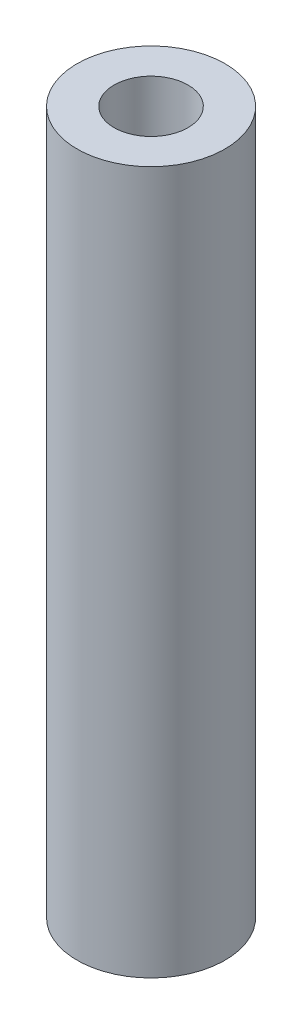
SolidWorks part; units mm, degrees
ref_plane "Front Plane" through (0, 0, 0) normal (0, 0, 1) x (1, 0, 0)
ref_plane "Top Plane" through (0, 0, 0) normal (0, 1, 0) x (1, 0, 0)
ref_plane "Right Plane" through (0, 0, 0) normal (1, 0, 0) x (0, 0, -1)
sketch "Sketch1" plane through (0, 0, 0) normal (0, 1, 0) x (1, 0, 0)
  circle A0 centre (0, 0) radius 2.54
  circle A1 centre (0, 0) radius 5.08
  dimension "D1" = 5.08
  dimension "D2" = 10.16
extrude "Boss-Extrude1" add sketch "Sketch1" along normal blind 48.26
